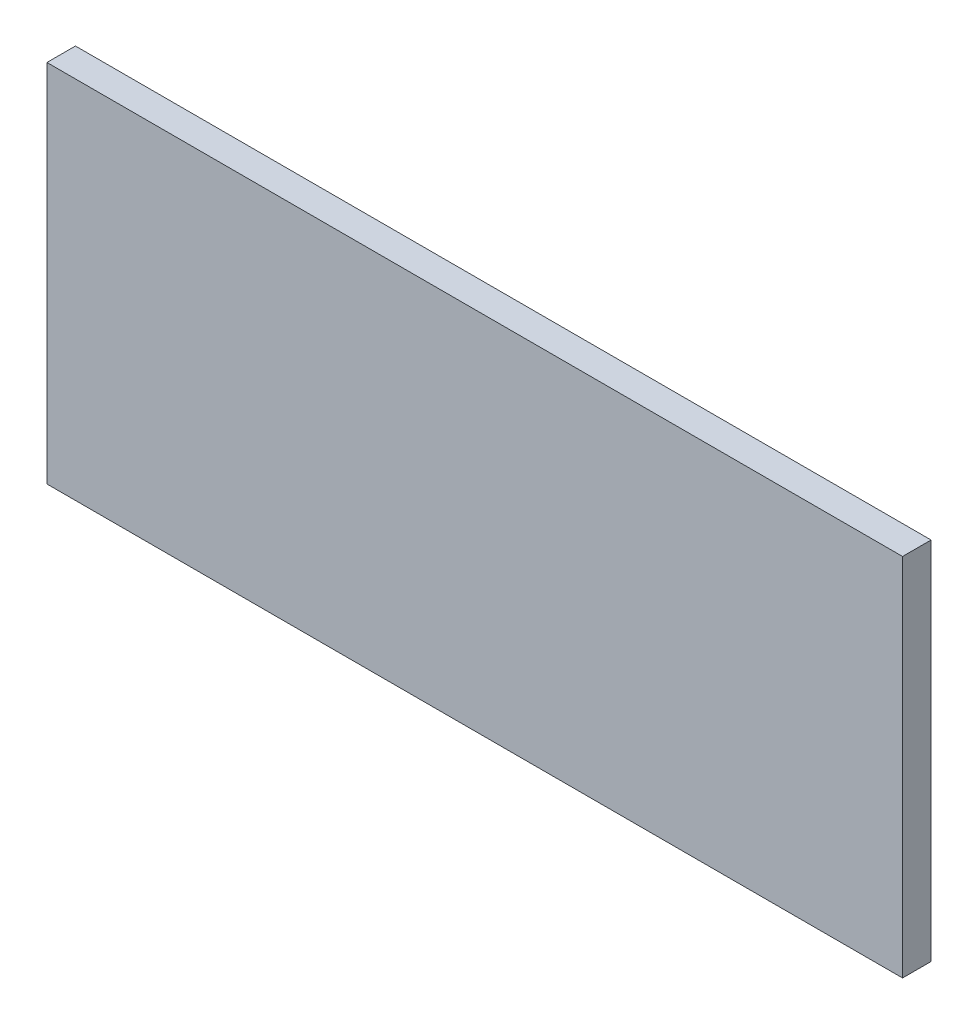
SolidWorks part; units mm, degrees
ref_plane "Front Plane" through (0, 0, 0) normal (0, 0, 1) x (1, 0, 0)
ref_plane "Top Plane" through (0, 0, 0) normal (0, 1, 0) x (1, 0, 0)
ref_plane "Right Plane" through (0, 0, 0) normal (1, 0, 0) x (0, 0, -1)
sketch "Sketch1" plane through (0, 0, 0) normal (0, 0, 1) x (1, 0, 0)
  line L1 (-75, 32) -> (75, 32)
  line L2 (-75, 32) -> (-75, -32)
  line L3 (-75, -32) -> (75, -32)
  line L4 (75, 32) -> (75, -32)
  dimension "D1" = 64
  dimension "D2" = 150
  dimension "D3" = 75
  dimension "D4" = 32
extrude "Boss-Extrude1" add sketch "Sketch1" along normal blind 5
